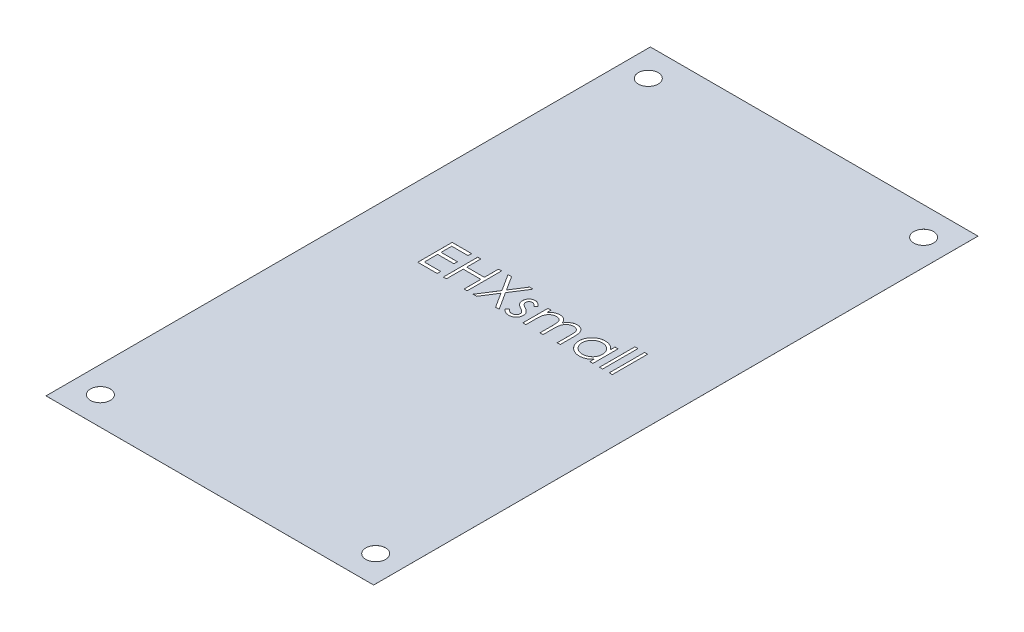
SolidWorks part; units mm, degrees
ref_plane "Front Plane" through (0, 0, 0) normal (0, 0, 1) x (1, 0, 0)
ref_plane "Top Plane" through (0, 0, 0) normal (0, 1, 0) x (1, 0, 0)
ref_plane "Right Plane" through (0, 0, 0) normal (1, 0, 0) x (0, 0, -1)
sketch "Sketch2" plane through (0, 0, 0) normal (0, 1, 0) x (1, 0, 0)
  line L1 (-30.226, -55.753) -> (30.226, -55.753)
  line L2 (-30.226, -55.753) -> (-30.226, 55.753)
  line L3 (-30.226, 55.753) -> (30.226, 55.753)
  line L4 (30.226, -55.753) -> (30.226, 55.753)
  line L5 (-30.226, -55.753) -> (30.226, 55.753) construction
  line L6 (-30.226, 55.753) -> (30.226, -55.753) construction
  point P0 (0, 0)
  dimension "D1" = 111.506
  dimension "D2" = 60.452
extrude "Boss-Extrude1" add sketch "Sketch2" along normal blind 0.0025
sketch "Sketch3" plane through (0, 0.0025, 0) normal (0, 1, 0) x (1, 0, 0)
  line L1 (-25.4, -50.546) -> (25.4, -50.546)
  line L2 (-25.4, -50.546) -> (-25.4, 50.546)
  line L3 (-25.4, 50.546) -> (25.4, 50.546)
  line L4 (25.4, -50.546) -> (25.4, 50.546)
  line L5 (-25.4, -50.546) -> (25.4, 50.546) construction
  line L6 (-25.4, 50.546) -> (25.4, -50.546) construction
  circle A0 centre (-25.4, 50.546) radius 1.8288
  circle A7 centre (25.4, 50.546) radius 1.8288
  circle A8 centre (25.4, -50.546) radius 1.8288
  circle A9 centre (-25.4, -50.546) radius 1.8288
  point P0 (0, 0)
  dimension "D3" = 3.6576
  dimension "D1" = 101.092
  dimension "D2" = 50.8
  dimension "D4" = 2
  dimension "D5" = 2
extrude "Cut-Extrude1" cut sketch "Sketch3" against normal through all contours A9 | A8 | A7 | A0
sketch "Sketch5" plane through (0, 0.0025, 0) normal (0, 1, 0) x (1, 0, 0)
  text T0 "EHXsmall\r\n" font "Century Gothic" height 6.35
extrude "Cut-Extrude2" cut sketch "Sketch5" against normal blind 2.54
